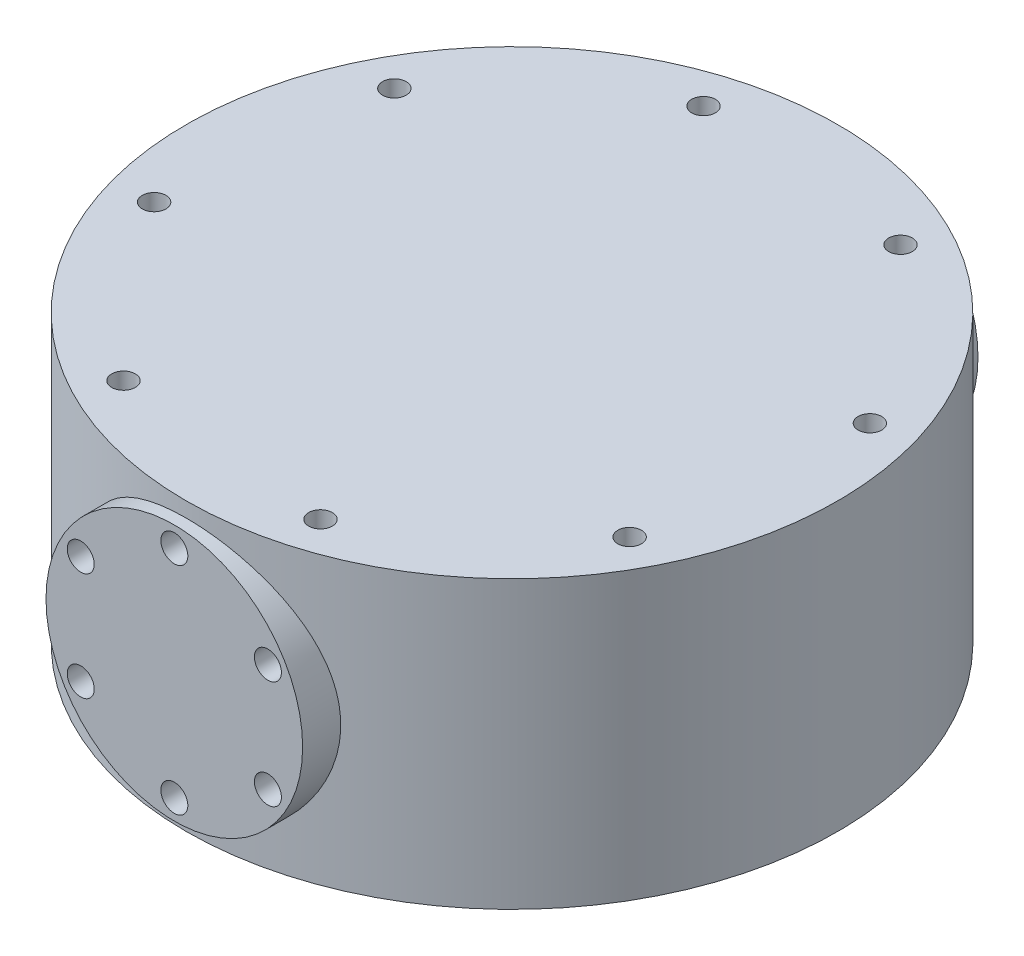
SolidWorks part; units mm, degrees
ref_plane "前视基准面" through (0, 0, 0) normal (0, 0, 1) x (1, 0, 0)
ref_plane "上视基准面" through (0, 0, 0) normal (0, 1, 0) x (1, 0, 0)
ref_plane "右视基准面" through (0, 0, 0) normal (1, 0, 0) x (0, 0, -1)
other "Configuration Table"
sketch "草图1" plane through (0, 0, 0) normal (0, 1, 0) x (1, 0, 0)
  circle A0 centre (0, 0) radius 48.25
  dimension "D1" = 96.5
extrude "凸台-拉伸2" add sketch "草图1" along normal blind 42.4 contours A0
sketch "草图2" plane through (0, 42.4, 0) normal (0, 1, 0) x (1, 0, 0)
  circle A0 centre (20.0519, 37.4723) radius 1.75
extrude "切除-拉伸1" cut sketch "草图2" against normal through all both and the other way through all contours A0
pattern_circular "阵列(圆周)2" count 8 over 360 about axis through (0, 0, 0) along (0, 1, 0) of "切除-拉伸1"
ref_plane "基准面1" through (0, 0, 0) normal (0, 0, 1) x (1, 0, 0)
sketch "草图4" plane through (0, 0, 0) normal (0, 0, 1) x (1, 0, 0)
  circle A0 centre (0, 21.2) radius 19
  circle A1 centre (0, 37.2) radius 2
  circle A2 centre (0, 37.2) radius 2
  dimension "D1" = 38
extrude "凸台-拉伸4" add sketch "草图4" along normal mid plane 100 contours A0
sketch "草图5" plane through (0, 0, 50) normal (0, 0, 1) x (1, 0, 0)
  circle A0 centre (0, 37.2) radius 2
extrude "切除-拉伸2" cut sketch "草图5" against normal through all both and the other way through all
pattern_circular "阵列(圆周)3" count 6 over 360 about axis through (0, 21.2, 0) along (0, 0, 1) of "切除-拉伸2"
